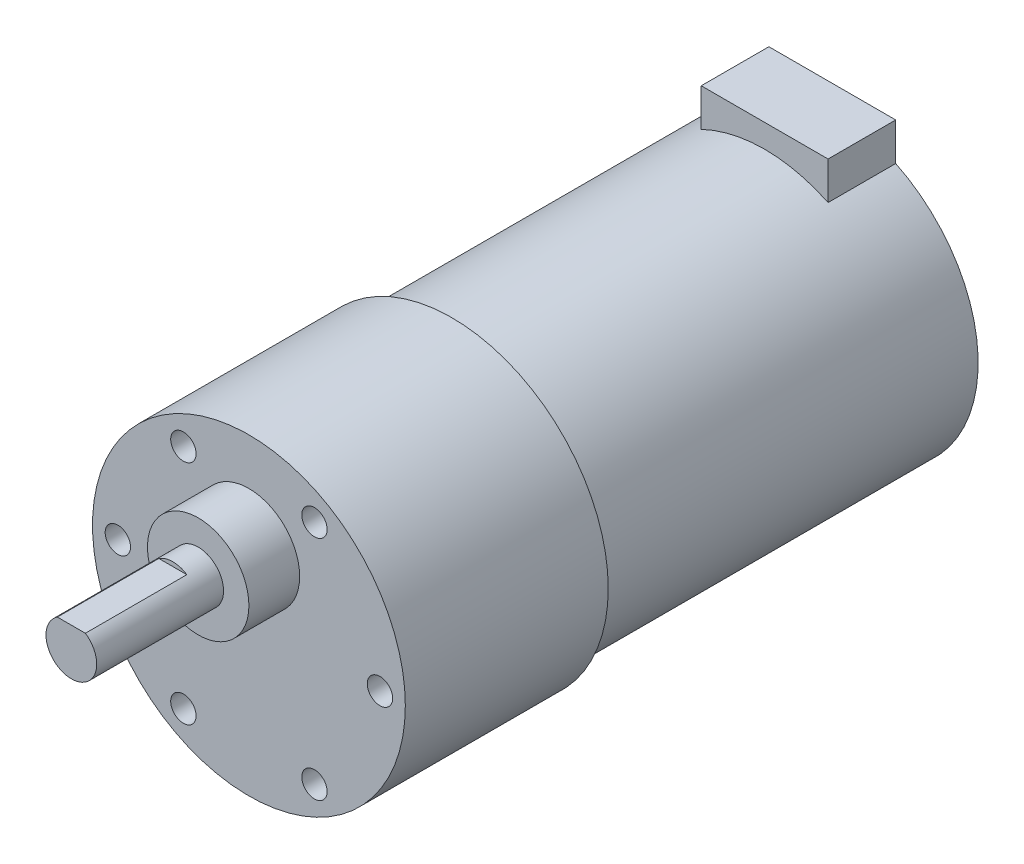
SolidWorks part; units mm, degrees
ref_plane "Front Plane" through (0, 0, 0) normal (0, 0, 1) x (1, 0, 0)
ref_plane "Top Plane" through (0, 0, 0) normal (0, 1, 0) x (1, 0, 0)
ref_plane "Right Plane" through (0, 0, 0) normal (1, 0, 0) x (0, 0, -1)
sketch "Sketch1" plane through (0, 0, 0) normal (0, 0, 1) x (1, 0, 0)
  circle A0 centre (0, 0) radius 18.5
  dimension "D1" = 37
extrude "Boss-Extrude1" add sketch "Sketch1" along normal blind 24
sketch "Sketch2" plane through (0, 0, 0) normal (0, 0, -1) x (-1, 0, 0)
  circle A0 centre (0, 0) radius 17.25
  dimension "D1" = 34.5
extrude "Boss-Extrude2" add sketch "Sketch2" along normal blind 45
sketch "Sketch3" plane through (0, 0, 24) normal (0, 0, 1) x (1, 0, 0)
  line L0 (0, 0) -> (0, 18.5) construction
  circle A0 centre (0, 0) radius 18.5 construction
  circle A1 centre (0, 7) radius 6
  dimension "D2" = 12
  dimension "D1" = 7
extrude "Boss-Extrude3" add sketch "Sketch3" along normal blind 6
sketch "Sketch4" plane through (0, 0, 30) normal (0, 0, 1) x (1, 0, 0)
  circle A0 centre (0, 7) radius 3
  circle A1 centre (0, 7) radius 6 construction
  dimension "D1" = 6
extrude "Boss-Extrude4" add sketch "Sketch4" along normal blind 15
sketch "Sketch5" plane through (0, 0, 45) normal (0, 0, 1) x (1, 0, 0)
  line L0 (-1.6583, 9.5) -> (1.6583, 9.5)
  line L1 (0, 9.5) -> (0, 4)
  circle A0 centre (0, 7) radius 3
  circle A1 centre (0, 7) radius 3 construction
  circle M1 centre (0, 7) radius 3
  dimension "D1" = 5.5
extrude "Cut-Extrude1" cut sketch "Sketch5" against normal blind 12 contours L0 M1
sketch "Sketch6" plane through (0, 0, 24) normal (0, 0, 1) x (1, 0, 0)
  line L0 (0, 18.5) -> (0, 0) construction
  line L1 (0, 0) -> (9.25, 16.0215) construction
  circle A0 centre (7.75, 13.4234) radius 1.5
  circle A3 centre (0, 0) radius 18.5 construction
  circle A4 centre (0, 0) radius 15.5 construction
  circle A5 centre (15.5, 0) radius 1.5
  circle A6 centre (7.75, -13.4234) radius 1.5
  circle A7 centre (-7.75, -13.4234) radius 1.5
  circle A8 centre (-15.5, 0) radius 1.5
  circle A9 centre (-7.75, 13.4234) radius 1.5
  point P21 (0, 0)
  dimension "D2" = 31
  dimension "D4" = 3
  dimension "D1" = 30
  dimension "D3" = 6
extrude "Cut-Extrude2" cut sketch "Sketch6" against normal blind 3
sketch "Sketch7" plane through (0, 0, 0) normal (0, 1, 0) x (1, 0, 0)
  line L0 (17.25, 45) -> (-17.25, 45) construction
  line L1 (-7.5, 45) -> (7.5, 45)
  line L2 (-7.5, 45) -> (-7.5, 37)
  line L3 (-7.5, 37) -> (7.5, 37)
  line L4 (7.5, 45) -> (7.5, 37)
  line L5 (0, -20.35) -> (0, 20.35) construction
  point P6 (0, 45)
  dimension "D1" = 8
  dimension "D2" = 15
extrude "Boss-Extrude5" add sketch "Sketch7" along normal blind 20
